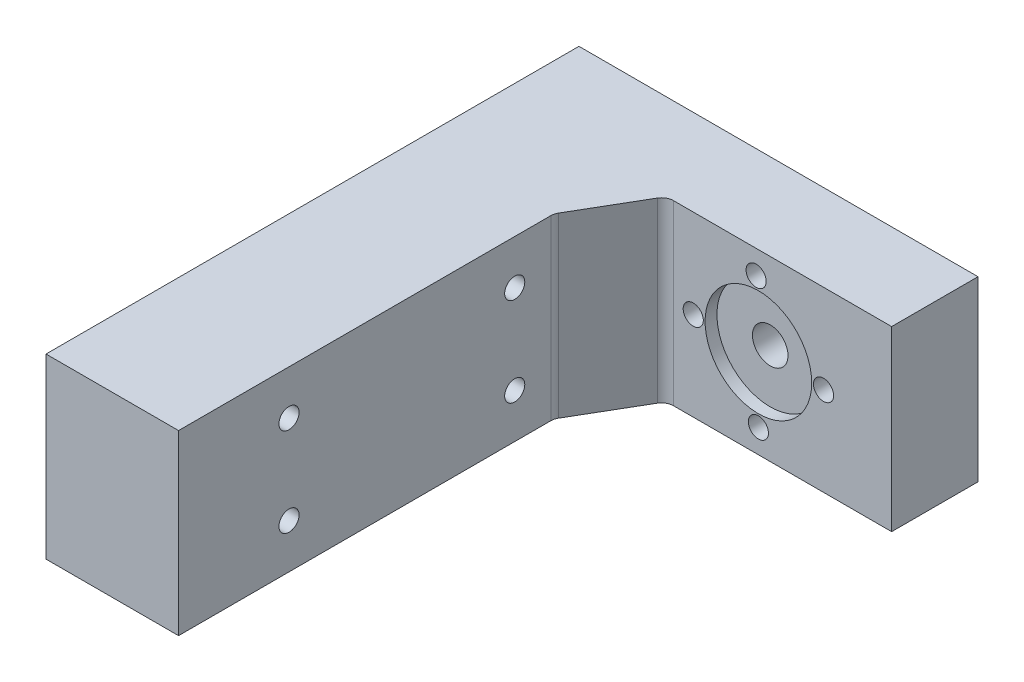
SolidWorks part; units mm, degrees
ref_plane "Front Plane" through (0, 0, 0) normal (1, 0, 0) x (0, 1, 0)
ref_plane "Top Plane" through (0, 0, 0) normal (0, 0, 1) x (0, 1, 0)
ref_plane "Right Plane" through (0, 0, 0) normal (0, 1, 0) x (-1, 0, 0)
sketch "Sketch2" plane through (0, 0, 0) normal (0, 1, 0) x (-1, 0, 0)
  line L0 (0, 0) -> (673.8533, 0)
  line L1 (673.8533, 0) -> (673.8533, 900)
  line L2 (673.8533, 900) -> (450, 900)
  line L3 (450, 900) -> (450, 145.8433)
  line L4 (450, 145.8433) -> (0, 145.8433)
  line L5 (0, 145.8433) -> (0, 0)
  dimension "D1" = 223.8533
  dimension "D3" = 145.8433
  dimension "D4" = 900
  dimension "D2" = 450
extrude "Boss-Extrude1" add sketch "Sketch2" along normal blind 300
sketch "Sketch3" plane through (0, 0, 145.8433) normal (0, 0, 1) x (1, 0, 0)
  circle A0 centre (-225, 150) radius 110 construction
  circle A1 centre (-335, 150) radius 17
  circle A2 centre (-228.823, 259.9335) radius 17
  circle A3 centre (-115, 150) radius 17
  circle A4 centre (-225, 40) radius 17
  circle A5 centre (-225, 150) radius 30
  dimension "D2" = 34
  dimension "D3" = 220
  dimension "D4" = 60
  dimension "D1" = 150
extrude "Cut-Extrude1" cut sketch "Sketch3" against normal through all
sketch "Sketch4" plane through (0, 0, 145.8433) normal (0, 0, 1) x (1, 0, 0)
  circle A0 centre (-225, 150) radius 90
  dimension "D1" = 180
extrude "Cut-Extrude2" cut sketch "Sketch4" against normal blind 20
sketch "Sketch5" plane through (-450, 0, 0) normal (1, 0, 0) x (0, 1, 0)
  circle A0 centre (75, 713.5) radius 17
  circle A1 centre (225, 713.5) radius 17
  circle A2 centre (75, 332.3433) radius 17
  circle A3 centre (225, 332.3433) radius 17
  dimension "D5" = 34
  dimension "D1" = 75
  dimension "D2" = 186.5
  dimension "D3" = 186.5
  dimension "D4" = 75
extrude "Cut-Extrude3" cut sketch "Sketch5" against normal through all
fillet "Chamfer1" radius 120 1 edges at (-450, 150, 145.8433)
sketch "Sketch7" plane through (0, 0, 145.8433) normal (0, 0, 1) x (1, 0, 0)
  circle A0 centre (-225, 150) radius 140
  dimension "D1" = 280
fillet "Fillet1" radius 20 2 edges at (-450, 150, 265.8433) (-380, 150, 145.8433)
equation "\"b\"= 30'Base dimensions for Mount (mm)"
equation "\"L1\"= 45'Height of Feature 1 (mm)"
equation "\"s\"= 18'Distance of Force from Feature 1 (mm)"
equation "\"FOS\"= 3'Given Factor of Safety"
equation "\"defl\"= 0.3'Given Deflection (mm)"
equation "\"E\"= 2350'Modulus of Elasticity (N/mm^2)"
equation "\"Yield\"= 45.2'Yield Stress of PLA Plastic (N/mm^2)"
equation "\"P\"= 300'Force Applied (N)"
equation "\"M_1\"= \"P\" * \"s\"'Moment applied to Feature 1 (N mm)"
equation "\"h1\"= ( ( 6 * \"M_1\" * ( \"L1\" ^ 2 ) ) / ( \"defl\" * \"b\" * \"E\" ) ) ^ ( 1 / 3 )'Height of Feature 1 (mm)"
equation "\"L_t\"= IIF ( ( ( \"h1\" + \"L_m\" ) - int ( \"h1\" + \"L_m\" ) ) > 0 , int ( \"h1\" + \"L_m\" ) + 1 , \"h1\" + \"L_m\" )'Length of Feature 2 (mm) (rounded with up with if statement)"
equation "\"L_m\"= 74.6'Length of Motor given (mm)"
equation "\"B_h\"= \"L_m\" / 4'Bolt Distance from vertical edges (mm)"
equation "\"B_w\"= \"b\" / 4'Bolt Distance from Horizontal edges (mm)"
equation "\"L_f\"= \"B_h\" + \"h1\" + ( \"4_M3\" / 2 )'Length of Feature 2 Free Part (mm)"
equation "\"M_2\"= \"P\" * ( \"L_t\" + \"s\" )'Moment applied to Feature 2 (N mm)"
equation "\"h2\"= ( ( 6 * \"M_2\" * ( \"L_f\" ^ 2 ) ) / ( \"defl\" * \"b\" * \"E\" ) ) ^ ( 1 / 3 )'Height of Feature 2 (N mm)"
equation "\"D1@Sketch2\"=\"h2\""
equation "\"D3@Sketch2\"=\"h1\""
equation "\"D4@Sketch2\"=\"L_t\""
equation "\"D1@Boss-Extrude1\"=\"b\""
equation "\"D2@Sketch2\"=\"L1\""
equation "\"D1@Sketch3\"=\"b\"/2"
equation "\"4_M3\"= 3.4'Diameter of Mounting Holes (mm)"
equation "\"D2@Sketch3\"=\"4_M3\""
equation "\"D1@Sketch5\"=\"B_w\""
equation "\"D2@Sketch5\"=\"B_h\""
equation "\"D3@Sketch5\"=\"B_h\""
equation "\"D4@Sketch5\"=\"B_w\""
equation "\"D5@Sketch5\"=\"4_M3\""
